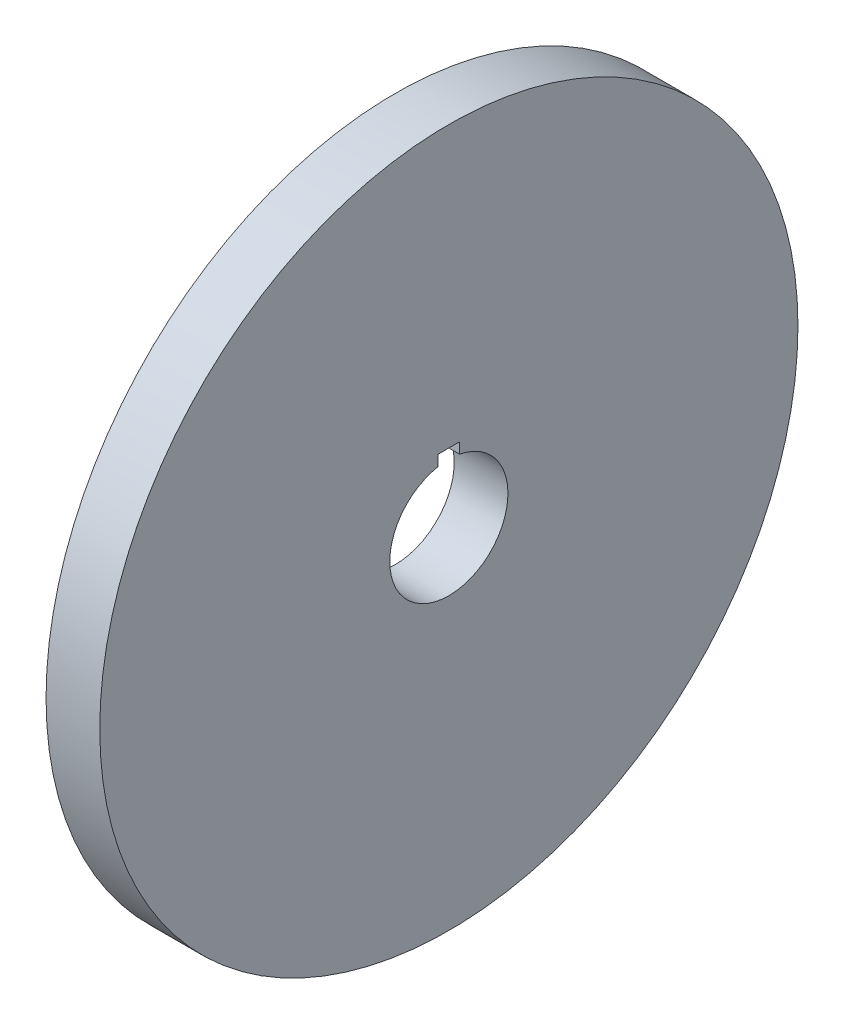
SolidWorks part; units mm, degrees
material "2024-T4"
ref_plane "Front Plane" through (0, 0, 0) normal (0, 0, 1) x (1, 0, 0)
ref_plane "Top Plane" through (0, 0, 0) normal (0, 1, 0) x (1, 0, 0)
ref_plane "Right Plane" through (0, 0, 0) normal (1, 0, 0) x (0, 0, -1)
sketch "Sketch1" plane through (0, 0, 0) normal (1, 0, 0) x (0, 0, -1)
  circle A1 centre (0, 0) radius 65
  dimension "D1" = 130
extrude "Boss-Extrude1" add sketch "Sketch1" along normal mid plane 10
sketch "Sketch3" plane through (5, 0, 0) normal (1, 0, 0) x (0, 0, -1)
  circle A0 centre (0, 0) radius 11
  dimension "D1" = 22
extrude "Cut-Extrude2" cut sketch "Sketch3" against normal through all
sketch "Sketch4" [suppressed] plane through (5, 0, 0) normal (1, 0, 0) x (0, 0, -1)
  circle A0 centre (0, 0) radius 7.5
  dimension "D1" = 15
extrude "Cut-Extrude3" [suppressed] cut sketch "Sketch4" against normal through all
sketch "Sketch5" plane through (5, 0, 0) normal (1, 0, 0) x (0, 0, -1)
  line L0 (0, 0) -> (0, 11) construction
  line L1 (-2, 10.8167) -> (-2, 12.8167)
  line L2 (-2, 12.8167) -> (2, 12.8167)
  line L3 (2, 10.8167) -> (2, 12.8167)
  circle A0 centre (0, 0) radius 11 construction
  arc A1 (2, 10.8167) -> (-2, 10.8167) centre (0, 0) ccw
  point P9 (0, 12.8167)
  dimension "D1" = 4
  dimension "D2" = 2
sketch "Sketch6" [suppressed] plane through (5, 0, 0) normal (1, 0, 0) x (0, 0, -1)
  line L0 (0, 0) -> (0, 7.5) construction
  line L1 (2, 9.2284) -> (-2, 9.2284)
  line L2 (-2, 9.2284) -> (-2, 7.2284)
  line L3 (2, 9.2284) -> (2, 7.2284)
  circle A0 centre (0, 0) radius 7.5 construction
  arc A1 (2, 7.2284) -> (-2, 7.2284) centre (0, 0) ccw
  point P8 (0, 9.2284)
  dimension "D1" = 4
  dimension "D2" = 2
extrude "Cut-Extrude4" [suppressed] cut sketch "Sketch6" against normal through all contours L1 L2 A1 L3
extrude "Cut-Extrude5" cut sketch "Sketch5" against normal through all contours L2 L3 A1 L1
